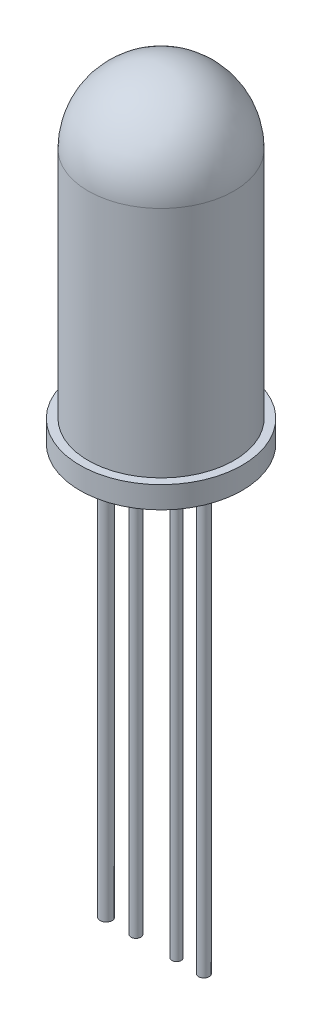
SolidWorks part; units mm, degrees
ref_plane "Front Plane" through (0, 0, 0) normal (0, 0, 1) x (1, 0, 0)
ref_plane "Top Plane" through (0, 0, 0) normal (0, 1, 0) x (1, 0, 0)
ref_plane "Right Plane" through (0, 0, 0) normal (1, 0, 0) x (0, 0, -1)
other "Center of Mass"
sketch "Sketch1" plane through (0, 0, 0) normal (0, 1, 0) x (1, 0, 0)
  circle A0 centre (0, 0) radius 2
  dimension "D1" = 4
extrude "Boss-Extrude1" add sketch "Sketch1" along normal blind 9
fillet "Fillet1" radius 2 1 edges at (0, 9, 2)
sketch "Sketch2" plane through (0, 0, 0) normal (0, -1, 0) x (1, 0, 0)
  circle A0 centre (0, 0) radius 2
  circle A1 centre (0, 0) radius 2.226
extrude "Boss-Extrude2" add sketch "Sketch2" against normal blind 0.6
sketch "Sketch3" plane through (0, 0, 0) normal (0, -1, 0) x (1, 0, 0)
  circle A0 centre (-0.689, 0) radius 0.1353
  circle A1 centre (-1.5072, 0) radius 0.1661
  circle A2 centre (0.4245, 0) radius 0.1292
  circle A3 centre (1.175, 0) radius 0.1476
extrude "Boss-Extrude3" add sketch "Sketch3" along normal blind 12 separate body
